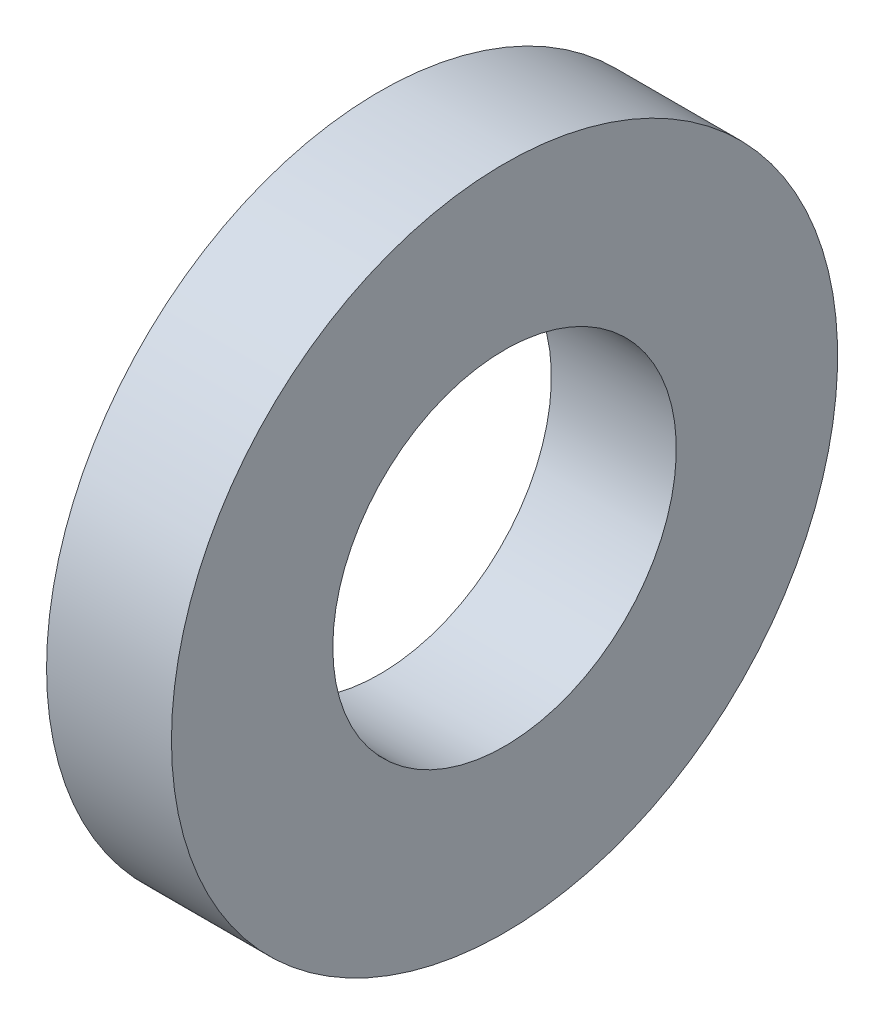
SolidWorks part; units mm, degrees
material "AISI Type 316L stainless steel"
ref_plane "Front Plane" through (0, 0, 0) normal (0, 0, 1) x (1, 0, 0)
ref_plane "Top Plane" through (0, 0, 0) normal (0, 1, 0) x (1, 0, 0)
ref_plane "Right Plane" through (0, 0, 0) normal (1, 0, 0) x (0, 0, -1)
sketch "Axial profile (mm)" plane through (0, 0, 0) normal (0, 0, 1) x (1, 0, 0)
  line L0 (-110, 0) -> (75, 0) construction
  line L1 (134.5, 1.65) -> (135.7, 1.65)
  line L2 (135.7, 1.65) -> (135.7, 3.2)
  line L3 (135.7, 3.2) -> (134.5, 3.2)
  line L4 (134.5, 3.2) -> (134.5, 1.65)
revolve "Full revolution" add sketch "Axial profile (mm)" angle 360 about L0
